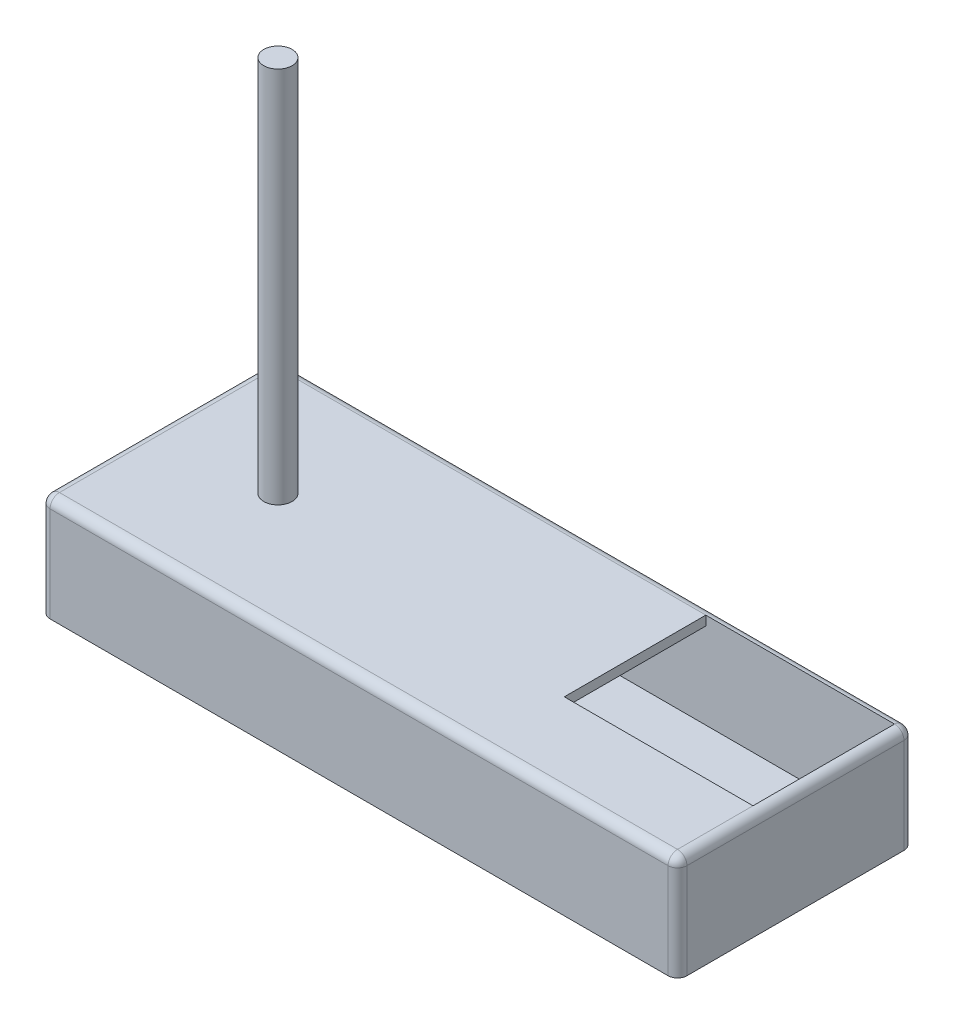
SolidWorks part; units mm, degrees
ref_plane "Front Plane" through (0, 0, 0) normal (0, 0, 1) x (1, 0, 0)
ref_plane "Top Plane" through (0, 0, 0) normal (0, 1, 0) x (1, 0, 0)
ref_plane "Right Plane" through (0, 0, 0) normal (1, 0, 0) x (0, 0, -1)
sketch "Sketch1" plane through (0, 0, 0) normal (0, 1, 0) x (1, 0, 0)
  line L1 (85.725, 31.75) -> (-85.725, 31.75)
  line L2 (85.725, 31.75) -> (85.725, -31.75)
  line L3 (85.725, -31.75) -> (-85.725, -31.75)
  line L4 (-85.725, 31.75) -> (-85.725, -31.75)
  line L5 (85.725, 31.75) -> (-85.725, -31.75) construction
  line L6 (85.725, -31.75) -> (-85.725, 31.75) construction
  point P0 (0, 0)
  point P8 (-89.8054, 15.1103)
  dimension "D1" = 63.5
  dimension "D2" = 171.45
extrude "Boss-Extrude1" add sketch "Sketch1" along normal blind 28.194
shell "Shell1" thickness 2.54
fillet "Fillet1" radius 2.54 1 edges at (0, 28.194, -31.75)
fillet "Fillet2" radius 2.54 1 edges at (0, 28.194, 31.75)
fillet "Fillet3" radius 2.54 5 edges at (-85.725, 12.827, -31.75) (-85.725, 27.4501, -31.0061) (-85.725, 12.827, 31.75) (-85.725, 27.4501, 31.0061) (-85.725, 28.194, 0)
fillet "Fillet4" radius 2.54 5 edges at (85.725, 12.827, 31.75) (85.725, 27.4501, 31.0061) (85.725, 12.827, -31.75) (85.725, 27.4501, -31.0061) (85.725, 28.194, 0)
sketch "Sketch7" plane through (0, 28.194, 0) normal (0, 1, 0) x (1, 0, 0)
  line L1 (83.185, 29.21) -> (32.385, 29.21)
  line L2 (83.185, 29.21) -> (83.185, -8.89)
  line L3 (83.185, -8.89) -> (32.385, -8.89)
  line L4 (32.385, 29.21) -> (32.385, -8.89)
  dimension "D1" = 38.1
  dimension "D2" = 50.8
extrude "Cut-Extrude4" cut sketch "Sketch7" against normal up to next contours L2 L1 L4 L3
sketch "Sketch13" plane through (0, 28.194, 0) normal (0, 1, 0) x (1, 0, 0)
  circle A0 centre (-53.5798, 0) radius 3.81
  dimension "D1" = 7.62
extrude "Boss-Extrude3" add sketch "Sketch13" along normal blind 101.6
sketch "Sketch24" plane through (-85.725, 0, 0) normal (-1, 0, 0) x (0, 0, 1)
  line L0 (-29.21, 25.654) -> (-29.21, 0) construction
  line L1 (29.21, 25.654) -> (-29.21, 25.654)
  line L2 (29.21, 25.654) -> (29.21, 2.7797)
  line L3 (29.21, 2.7797) -> (-29.21, 2.7797)
  line L4 (-29.21, 25.654) -> (-29.21, 2.7797)
extrude "Cut-Extrude8" cut sketch "Sketch24" against normal up to next
